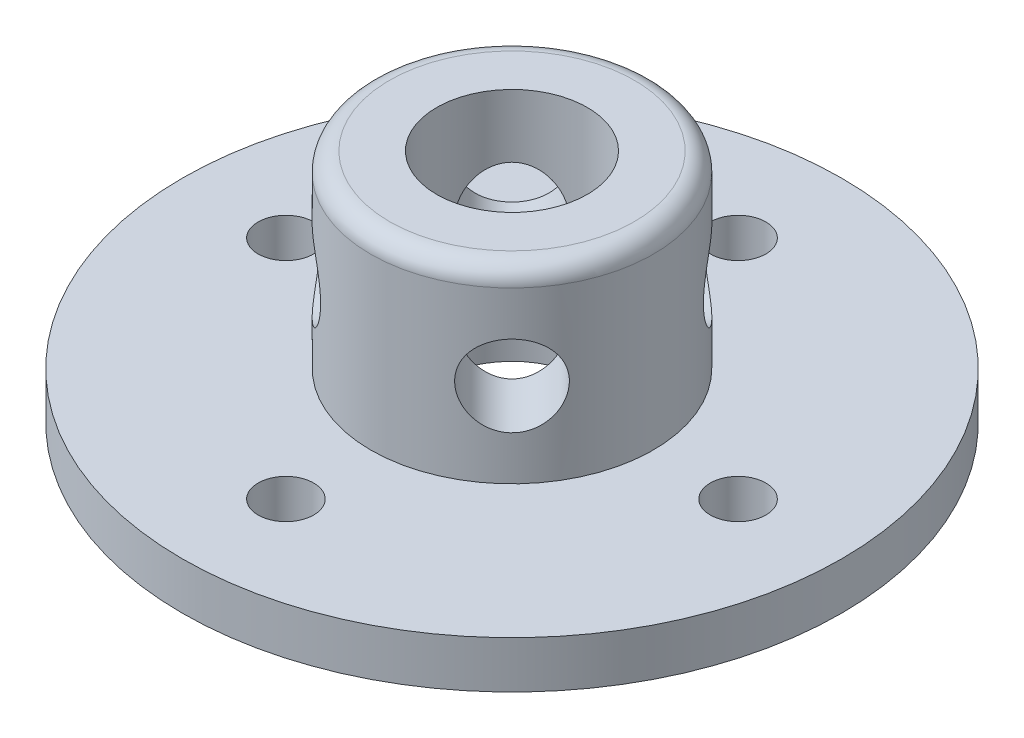
SolidWorks part; units mm, degrees
ref_plane "Front Plane" through (0, 0, 0) normal (0, 0, 1) x (1, 0, 0)
ref_plane "Top Plane" through (0, 0, 0) normal (0, 1, 0) x (1, 0, 0)
ref_plane "Right Plane" through (0, 0, 0) normal (1, 0, 0) x (0, 0, -1)
sketch "Sketch2" plane through (0, 0, 0) normal (0, 1, 0) x (1, 0, 0)
  line L0 (0, 20.1826) -> (0, -19.3833) construction
  line L1 (-36.8042, 0) -> (40.004, 0) construction
  circle A3 centre (0, 0) radius 4
  circle A4 centre (0, 0) radius 17.5
  circle A5 centre (0, 12) radius 1.475
  circle A6 centre (12, 0) radius 1.475
  circle A7 centre (0, -12) radius 1.475
  circle A8 centre (-12, 0) radius 1.475
  point P20 (0, 0)
  dimension "D2" = 8
  dimension "D3" = 35
  dimension "D4" = 12
  dimension "D5" = 2.95
  dimension "D6" = 4
extrude "Boss-Extrude1" add sketch "Sketch2" along normal blind 2.5 contours A4 A8 A7 A6 A5 A3
sketch "Sketch3" plane through (0, 2.5, 0) normal (0, 1, 0) x (1, 0, 0)
  line L0 (-17.5, 0) -> (17.5, 0) construction
  line L1 (0, 17.5) -> (0, -17.5) construction
  circle A0 centre (0, 0) radius 4 construction
  circle A1 centre (0, 0) radius 4
  circle A2 centre (0, 0) radius 7.5
  circle A3 centre (0, 0) radius 17.5 construction
  dimension "D3" = 15
extrude "Boss-Extrude2" add sketch "Sketch3" along normal blind 10
fillet "Fillet1" radius 1 1 edges at (0, 12.5, 7.5)
ref_plane "Plane1" through (5.3033, 0, 5.3033) normal (0.7071, 0, 0.7071) x (0, -1, 0)
sketch "Sketch7" plane through (5.3033, 0, 5.3033) normal (0.7071, 0, 0.7071) x (0, -1, 0)
  line L0 (-7, 7.5) -> (-7, -7.5) construction
  line L1 (-2.5, 7.5) -> (-11.5, 7.5) construction
  line L2 (-11.5, -7.5) -> (-2.5, -7.5) construction
  line L3 (-11.5, 0) -> (-2.5, 0) construction
  line L4 (-11.5, -7.5) -> (-11.5, 7.5) construction
  line L5 (-2.5, 7.5) -> (-2.5, -7.5) construction
  circle A0 centre (-7, 0) radius 2.1534
extrude "Cut-Extrude7" cut sketch "Sketch7" against normal blind 5 contours A0
pattern_circular "CirPattern2" count 4 over 360 about axis through (0, 12.5, 0) along (0, -1, 0) of "Cut-Extrude7"
sketch "Sketch8" plane through (0, 0, 0) normal (0, -1, 0) x (1, 0, 0)
